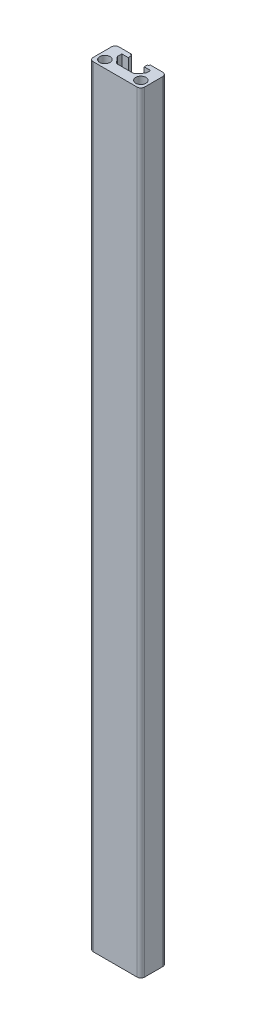
SolidWorks part; units mm, degrees
ref_plane "前视基准面" through (0, 0, 0) normal (0, 0, 1) x (1, 0, 0)
ref_plane "上视基准面" through (0, 0, 0) normal (0, 1, 0) x (1, 0, 0)
ref_plane "右视基准面" through (0, 0, 0) normal (1, 0, 0) x (0, 0, -1)
sketch "草图1" plane through (0, 0, 0) normal (0, 1, 0) x (1, 0, 0)
  line L0 (0, 0) -> (20, 0)
  line L1 (20, 0) -> (20, 10)
  line L2 (20, 10) -> (13.65, 10)
  line L3 (0, 10) -> (0, 0)
  line L4 (6.35, 10) -> (6.35, 9.5104)
  line L5 (6.35, 9.5104) -> (6.9, 9.5104)
  line L6 (6.9, 9.5104) -> (6.9, 8.2)
  line L7 (6.9, 8.2) -> (4.4, 8.2)
  line L8 (4.4, 8.2) -> (4.4, 6.4475)
  line L9 (4.4, 6.4475) -> (6.5873, 3.9)
  line L11 (15.6, 6.4475) -> (15.6, 8.2)
  line L12 (15.6, 8.2) -> (13.1, 8.2)
  line L13 (13.1, 8.2) -> (13.1, 9.5104)
  line L14 (13.1, 9.5104) -> (13.65, 9.5104)
  line L15 (13.65, 9.5104) -> (13.65, 10)
  line L16 (6.35, 10) -> (0, 10)
  line L17 (10, 0) -> (10, 13.7687) construction
  line L18 (6.5873, 3.9) -> (13.4127, 3.9)
  line L19 (13.4127, 3.9) -> (15.6, 6.4475)
  circle A0 centre (3, 3) radius 2
  circle A1 centre (17, 3) radius 2
  point P12 (10, 3.9)
  dimension "D8" = 4
  dimension "D1" = 20
  dimension "D2" = 10
  dimension "D3" = 7.3
  dimension "D4" = 6.2
  dimension "D5" = 1.8
  dimension "D6" = 4.3
  dimension "D7" = 11.2
  dimension "D9" = 3
  dimension "D10" = 14
extrude "凸台-拉伸1" add sketch "草图1" along normal blind 300
fillet "圆角1" radius 1.5 4 edges at (0, 150, -10) (0, 150, 0) (20, 150, -10) (20, 150, 0)
